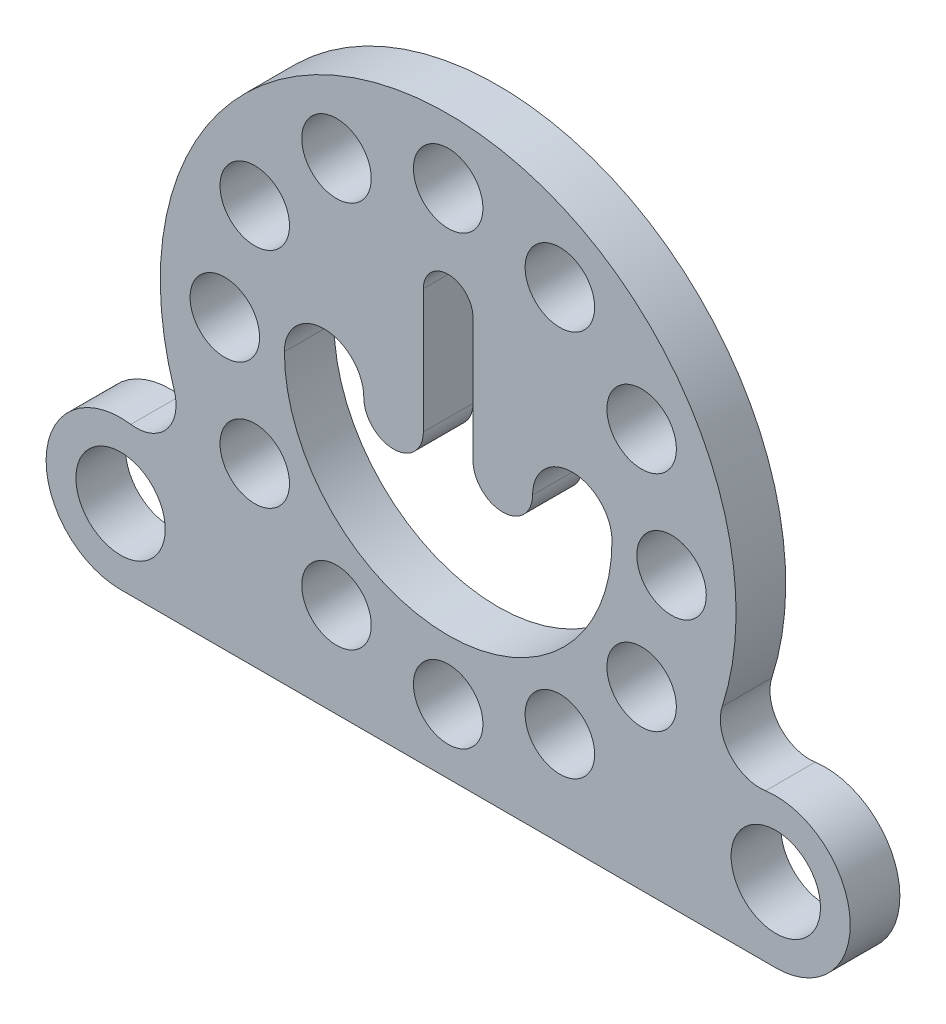
SolidWorks part; units mm, degrees
ref_plane "Alzado" through (0, 0, 0) normal (0, 0, 1) x (1, 0, 0)
ref_plane "Planta" through (0, 0, 0) normal (0, 1, 0) x (1, 0, 0)
ref_plane "Vista lateral" through (0, 0, 0) normal (1, 0, 0) x (0, 0, -1)
sketch "Croquis1" plane through (0, 0, 0) normal (0, 0, 1) x (1, 0, 0)
  line L0 (0, 0) -> (0, -58) construction
  line L1 (66, -58) -> (-66, -58)
  line L2 (-5, 25) -> (-5, 0)
  line L3 (5, 25) -> (5, 0)
  circle A0 centre (0, 0) radius 25 construction
  circle A1 centre (0, 0) radius 45 construction
  circle A2 centre (0, 0) radius 58
  circle A4 centre (0, 45) radius 7
  circle A5 centre (22.5, 38.9711) radius 7
  circle A6 centre (38.9711, 22.5) radius 7
  circle A7 centre (45, 0) radius 7
  circle A8 centre (38.9711, -22.5) radius 7
  circle A9 centre (22.5, -38.9711) radius 7
  circle A10 centre (0, -45) radius 7
  circle A11 centre (-22.5, -38.9711) radius 7
  circle A12 centre (-38.9711, -22.5) radius 7
  circle A13 centre (-45, 0) radius 7
  circle A14 centre (-38.9711, 22.5) radius 7
  circle A15 centre (-22.5, 38.9711) radius 7
  arc A16 (-63.9302, -28.1435) -> (-66, -58) centre (-66, -43) ccw
  circle A17 centre (-66, -43) radius 9
  arc A18 (-55.211, -17.7691) -> (-63.9302, -28.1435) centre (-62.8264, -20.22) cw
  arc A19 (25, 0) -> (-25, 0) centre (0, 0) cw construction
  arc A20 (-33, 0) -> (33, 0) centre (0, 0) ccw
  arc A22 (-17, 0) -> (-33, 0) centre (-25, 0) ccw
  arc A23 (33, 0) -> (17, 0) centre (25, 0) ccw
  arc A24 (5, 25) -> (-5, 25) centre (0, 25) ccw
  arc A25 (-17, 0) -> (-5, 0) centre (-11, 0) ccw
  arc A26 (5, 0) -> (17, 0) centre (11, 0) ccw
  circle A27 centre (66, -43) radius 9
  arc A28 (55.211, -17.7691) -> (63.9302, -28.1435) centre (62.8264, -20.22) ccw
  arc A29 (63.9302, -28.1435) -> (66, -58) centre (66, -43) cw
  point P32 (0, 0)
  point P40 (0, -25)
  dimension "D1" = 50
  dimension "D2" = 90
  dimension "D3" = 116
  dimension "D4" = 14
  dimension "D8" = 15
  dimension "D9" = 18
  dimension "D10" = 8
  dimension "D11" = 8
  dimension "D12" = 6
  dimension "D13" = 5
  dimension "D14" = 33
  dimension "D6" = 66
  dimension "D7" = 15
  dimension "D5" = 12
extrude "Saliente-Extruir1" add sketch "Croquis1" along normal blind 10 contours A2 A15 A14 A13 A12 A11 A10 A9 A8 A7 A6 A5 A4 L3 A26 A23 A20 A22 A25 L2 A24 | A29 A28 A2 L1 A27 | A2 A18 A16 L1 A17
